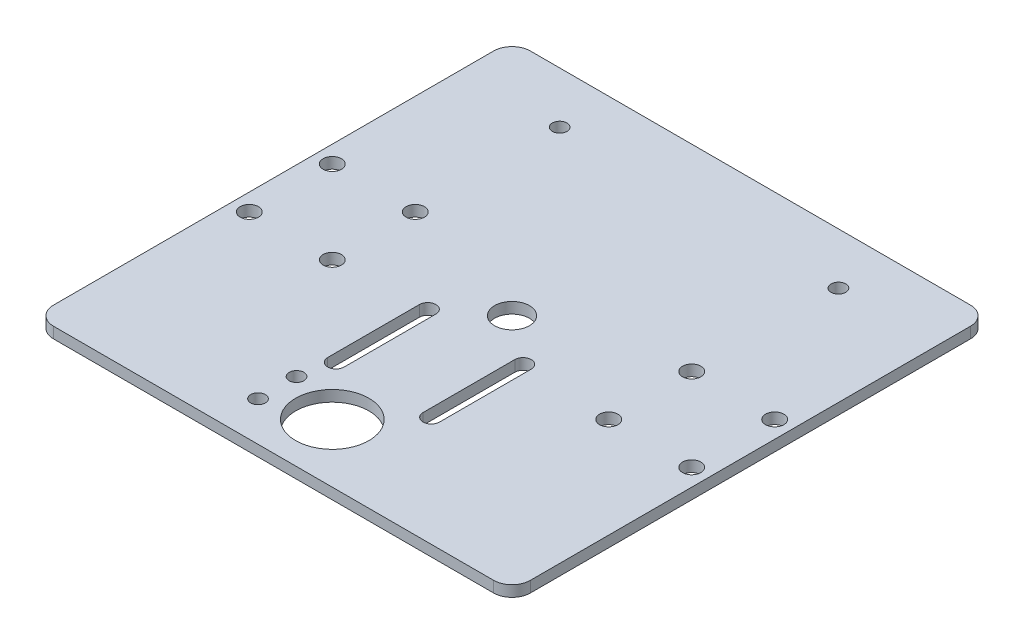
SolidWorks part; units mm, degrees
ref_plane "Front Plane" through (0, 0, 0) normal (0, 0, 1) x (1, 0, 0)
ref_plane "Top Plane" through (0, 0, 0) normal (0, 1, 0) x (1, 0, 0)
ref_plane "Right Plane" through (0, 0, 0) normal (1, 0, 0) x (0, 0, -1)
sketch "Sketch1" plane through (0, 0, 0) normal (0, 1, 0) x (1, 0, 0)
  line L1 (-65, 65) -> (65, 65)
  line L2 (-65, 65) -> (-65, -65)
  line L3 (-65, -65) -> (65, -65)
  line L4 (65, 65) -> (65, -65)
  line L5 (-65, 65) -> (65, -65) construction
  line L6 (-65, -65) -> (65, 65) construction
  point P0 (0, 0)
  dimension "D1" = 130
  dimension "D2" = 130
extrude "Boss-Extrude1" add sketch "Sketch1" along normal blind 3
fillet "Fillet1" radius 5 4 edges at (65, 1.5, 65) (65, 1.5, -65) (-65, 1.5, -65) (-65, 1.5, 65)
sketch "Sketch2" plane through (0, 0, 0) normal (0, 1, 0) x (1, 0, 0)
  line L0 (60, 65) -> (-60, 65) construction
  line L1 (0, 0) -> (-49, 0) construction
  line L2 (-65, 60) -> (-65, -60) construction
  line L3 (-60.3137, 11.3137) -> (-37.6863, 11.3137) construction
  line L4 (-60.3137, 11.3137) -> (-60.3137, -11.3137) construction
  line L5 (-60.3137, -11.3137) -> (-37.6863, -11.3137) construction
  line L6 (-37.6863, 11.3137) -> (-37.6863, -11.3137) construction
  line L7 (-60.3137, 11.3137) -> (-37.6863, -11.3137) construction
  line L8 (-60.3137, -11.3137) -> (-37.6863, 11.3137) construction
  circle A0 centre (0, 0) radius 4.75
  circle A1 centre (-49, 0) radius 16 construction
  dimension "D2" = 9.5
  dimension "D3" = 32
  dimension "D1" = 65
extrude "Cut-Extrude1" cut sketch "Sketch2" along normal through all
hole_wizard "Ø5.0 (5) Diameter Hole1" positions "Sketch4" profile "Sketch3" hole size "Ø5.0" standard "ANSI Metric" end condition through all
sketch "Sketch4" plane through (0, 0, 0) normal (0, -1, 0) x (-1, 0, 0)
  point P0 (60.3137, 11.3137)
  point P2 (60.3137, -11.3137)
  point P4 (37.6863, -11.3137)
  point P6 (37.6863, 11.3137)
sketch "Sketch3" plane through (-60.3137, 0, -11.3137) normal (1, 0, 0) x (0, 0, -1)
  line L0 (0, 0) -> (0, 3)
  line L1 (0, 3) -> (2.5, 3)
  line L2 (2.5, 3) -> (2.5, 0)
  line L5 (2.5, 0) -> (0, 0)
  line L11 (0, -6.35) -> (0, 107.95) construction
  dimension "Thru Hole Dia." = 5
  dimension "Thru Hole Depth" = 3
mirror "Mirror1" about plane through (0, 0, 0) normal (1, 0, 0) of "Ø5.0 (5) Diameter Hole1"
hole_wizard "Ø4.0 (4) Diameter Hole1" positions "Sketch7" profile "Sketch6" hole size "Ø4.0" standard "ANSI Metric" end condition through all
sketch "Sketch7" plane through (0, 3, 0) normal (0, 1, 0) x (1, 0, 0)
  line L0 (38, 51) -> (-38, 51) construction
  line L3 (0, 51) -> (0, 0) construction
  line L6 (60, 65) -> (-60, 65) construction
  point P0 (38, 51)
  point P2 (-38, 51)
  dimension "D2" = 76
  dimension "D1" = 14
sketch "Sketch6" plane through (38, 3, -51) normal (1, 0, 0) x (0, 0, 1)
  line L0 (0, 0) -> (0, 3)
  line L1 (0, 3) -> (2, 3)
  line L2 (2, 3) -> (2, 0)
  line L5 (2, 0) -> (0, 0)
  line L11 (0, -6.35) -> (0, 107.95) construction
  dimension "Thru Hole Dia." = 4
  dimension "Thru Hole Depth" = 3
sketch "Sketch8" plane through (0, 0, 0) normal (0, 1, 0) x (1, 0, 0)
  line L0 (13, -35) -> (13, -10) construction
  line L1 (10.75, -35) -> (10.75, -10)
  line L2 (15.25, -35) -> (15.25, -10)
  line L3 (0, 0) -> (0, -49) construction
  line L5 (-13, -35) -> (-13, -10) construction
  line L6 (-10.75, -35) -> (-10.75, -10)
  line L7 (-15.25, -35) -> (-15.25, -10)
  line L8 (0, -49) -> (-15, -49) construction
  line L9 (-15, -54.25) -> (-15, -43.75) construction
  arc A0 (10.75, -35) -> (15.25, -35) centre (13, -35) ccw
  arc A1 (15.25, -10) -> (10.75, -10) centre (13, -10) ccw
  arc A2 (-10.75, -35) -> (-15.25, -35) centre (-13, -35) cw
  arc A3 (-15.25, -10) -> (-10.75, -10) centre (-13, -10) cw
  circle A4 centre (0, -49) radius 10
  point P2 (13, -22.5)
  point P14 (-13, -22.5)
  dimension "D2" = 2.25
  dimension "D6" = 20
  dimension "D1" = 13
  dimension "D3" = 25
  dimension "D4" = 10
  dimension "D5" = 49
  dimension "D7" = 10.5
  dimension "D8" = 15
extrude "Cut-Extrude2" cut sketch "Sketch8" along normal through all
hole_wizard "Ø4.0 (4) Diameter Hole2" positions "Sketch10" profile "Sketch9" hole size "Ø4.0" standard "ANSI Metric" end condition through all
sketch "Sketch10" plane through (0, 3, 0) normal (0, 1, 0) x (1, 0, 0)
  point P0 (-15, -54.25)
  point P3 (-15, -43.75)
sketch "Sketch9" plane through (-15, 3, 54.25) normal (1, 0, 0) x (0, 0, 1)
  line L0 (0, 0) -> (0, 3)
  line L1 (0, 3) -> (2, 3)
  line L2 (2, 3) -> (2, 0)
  line L5 (2, 0) -> (0, 0)
  line L11 (0, -6.35) -> (0, 107.95) construction
  dimension "Thru Hole Dia." = 4
  dimension "Thru Hole Depth" = 3
equation "\"a\"= 130"
equation "\"b\"= 130"
equation "\"c\"= 3"
equation "\"D1@Boss-Extrude1\"=\"c\""
equation "\"D2@Sketch1\"=\"b\""
equation "\"D1@Sketch1\"=\"a\""
equation "\"e\"= 76"
equation "\"f\"=14"
equation "\"D2@Sketch7\"=\"e\""
equation "\"D1@Sketch7\"=\"f\""
equation "\"D1@Sketch2\"=\"b\"/2"
